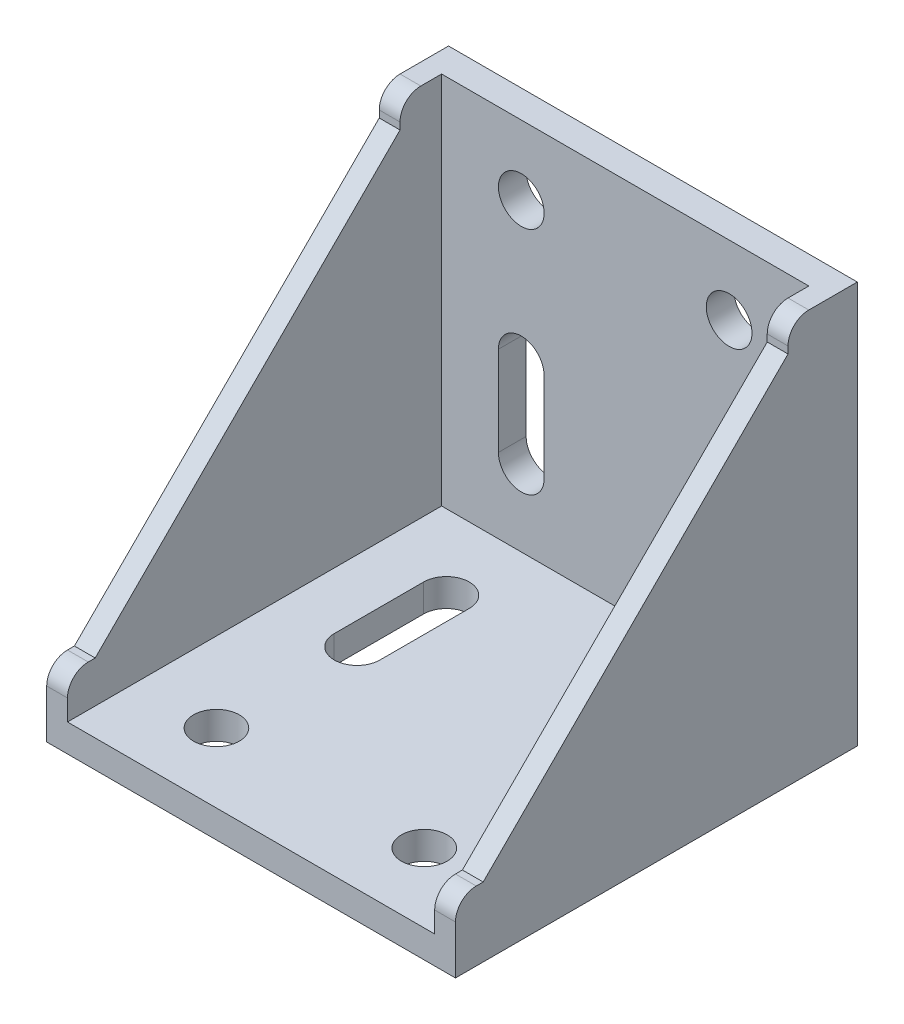
SolidWorks part; units mm, degrees
other "Камера1"
material "3.0526 (EN-AW 3005)"
ref_plane "Спереди" through (0, 0, 0) normal (0, 0, 1) x (1, 0, 0)
ref_plane "Сверху" through (0, 0, 0) normal (0, 1, 0) x (1, 0, 0)
ref_plane "Справа" through (0, 0, 0) normal (1, 0, 0) x (0, 0, -1)
sketch "Эскиз1" plane through (0, 0, 0) normal (0, 0, 1) x (1, 0, 0)
  line L0 (18.3, -14.2) -> (18.3, -1.3)
  line L1 (-29.5, 29) -> (29.5, 29)
  line L2 (-29.5, 29) -> (-29.5, -29)
  line L3 (-29.5, -29) -> (29.5, -29)
  line L4 (29.5, 29) -> (29.5, -29)
  line L5 (-29.5, 29) -> (29.5, -29) construction
  line L6 (-29.5, -29) -> (29.5, 29) construction
  line L7 (0, 41.4674) -> (0, -37.8406) construction
  line L8 (-18.3, -1.3) -> (-18.3, -14.2)
  line L9 (-11.7, -14.2) -> (-11.7, -1.3)
  line L10 (11.7, -1.3) -> (11.7, -14.2)
  circle A0 centre (-15, 19) radius 3.3
  circle A1 centre (15, 19) radius 3.3
  arc A2 (-11.7, -1.3) -> (-18.3, -1.3) centre (-15, -1.3) ccw
  arc A3 (-18.3, -14.2) -> (-11.7, -14.2) centre (-15, -14.2) ccw
  arc A4 (18.3, -1.3) -> (11.7, -1.3) centre (15, -1.3) ccw
  arc A5 (11.7, -14.2) -> (18.3, -14.2) centre (15, -14.2) ccw
  point P0 (0, 0)
  dimension "D1" = 59
  dimension "D2" = 58
  dimension "D5" = 30
  dimension "D6" = 10
extrude "Бобышка-Вытянуть1" add sketch "Эскиз1" along normal blind 4
ref_plane "Плоскость1" through (0, -29, 0) normal (0, -1, 0) x (-1, 0, 0)
sketch "Эскиз4" plane through (0, -29, 0) normal (0, -1, 0) x (-1, 0, 0)
  line L3 (-29.5, 0) -> (29.5, 0)
  line L11 (0, -70.4674) -> (0, 8.8406) construction
  line L12 (-29.5, 0) -> (29.5, -58) construction
  line L13 (-29.5, -58) -> (29.5, 0) construction
  line L14 (11.7, -27.7) -> (11.7, -14.8)
  line L15 (-11.7, -14.8) -> (-11.7, -27.7)
  line L16 (-18.3, -27.7) -> (-18.3, -14.8)
  line L17 (29.5, -58) -> (29.5, 0)
  line L18 (-29.5, -58) -> (-29.5, 0)
  line L19 (-29.5, -58) -> (29.5, -58)
  line L20 (18.3, -14.8) -> (18.3, -27.7)
  arc A6 (11.7, -14.8) -> (18.3, -14.8) centre (15, -14.8) cw
  arc A7 (18.3, -27.7) -> (11.7, -27.7) centre (15, -27.7) cw
  arc A8 (-18.3, -14.8) -> (-11.7, -14.8) centre (-15, -14.8) cw
  arc A9 (-11.7, -27.7) -> (-18.3, -27.7) centre (-15, -27.7) cw
  circle A10 centre (15, -48) radius 3.3
  circle A11 centre (-15, -48) radius 3.3
  point P60 (0, -29)
  dimension "D3" = 29
  dimension "D1" = 59
  dimension "D2" = 58
ref_plane "Плоскость4" through (-29.5, 0, 0) normal (-1, 0, 0) x (0, 0, 1)
sketch "Эскиз5" plane through (-29.5, 0, 0) normal (-1, 0, 0) x (0, 0, 1)
  line L0 (0, 29) -> (7, 29)
  line L1 (10, 26) -> (10, 25)
  line L2 (10, 25) -> (54, -19)
  line L3 (55, -19) -> (54, -19)
  line L4 (58, -29) -> (58, -22)
  line L5 (0, 29) -> (0, -29)
  line L6 (0, -29) -> (58, -29)
  arc A0 (7, 29) -> (10, 26) centre (7, 26) cw
  arc A2 (58, -22) -> (55, -19) centre (55, -22) ccw
  point P6 (10, 29)
  dimension "D3" = 3
  dimension "D1" = 10
  dimension "D2" = 4
extrude "Бобышка-Вытянуть3" add sketch "Эскиз5" against normal blind 3
ref_plane "Плоскость5" through (29.5, 0, 0) normal (1, 0, 0) x (0, 0, -1)
sketch "Эскиз6" plane through (29.5, 0, 0) normal (1, 0, 0) x (0, 0, -1)
  line L5 (0, 29) -> (0, -29)
  line L7 (-10, 26) -> (-10, 25)
  line L8 (0, 29) -> (-7, 29)
  line L9 (0, -29) -> (-58, -29)
  line L10 (-58, -29) -> (-58, -22)
  line L11 (-55, -19) -> (-54, -19)
  line L12 (-10, 25) -> (-54, -19)
  arc A1 (-7, 29) -> (-10, 26) centre (-7, 26) ccw
  arc A3 (-58, -22) -> (-55, -19) centre (-55, -22) cw
  point P6 (10, 29)
  dimension "D1" = 10
extrude "Бобышка-Вытянуть6" add sketch "Эскиз6" against normal blind 3
extrude "Бобышка-Вытянуть7" add sketch "Эскиз4" against normal blind 4
